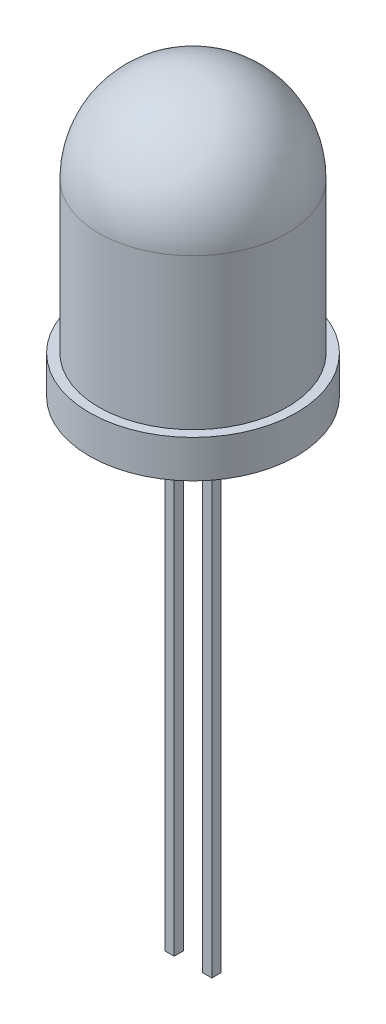
SolidWorks part; units mm, degrees
ref_plane "Front Plane" through (0, 0, 0) normal (0, 0, 1) x (1, 0, 0)
ref_plane "Top Plane" through (0, 0, 0) normal (0, 1, 0) x (1, 0, 0)
ref_plane "Right Plane" through (0, 0, 0) normal (1, 0, 0) x (0, 0, -1)
sketch "Sketch1" plane through (0, 0, 0) normal (0, 1, 0) x (1, 0, 0)
  circle A0 centre (0, 0) radius 5.5
  dimension "D1" = 11
extrude "Boss-Extrude1" add sketch "Sketch1" along normal blind 2
sketch "Sketch2" plane through (0, 2, 0) normal (0, 1, 0) x (1, 0, 0)
  circle A0 centre (0, 0) radius 5
  circle A1 centre (0, 0) radius 5.5 construction
  dimension "D1" = 0.5
extrude "Boss-Extrude2" add sketch "Sketch2" along normal blind 8
sketch "Sketch3" plane through (0, 10, 0) normal (0, 1, 0) x (1, 0, 0)
  line L0 (0, 5) -> (0, -5) construction
  line L1 (0, 5) -> (0, -5)
  circle A0 centre (0, 0) radius 5 construction
  circle A1 centre (0, 0) radius 5 construction
  arc A2 (0, 5) -> (0, -5) centre (0, 0) cw
revolve "Revolve1" add sketch "Sketch3" angle 180 about L1
sketch "Sketch4" plane through (0, 0, 0) normal (0, -1, 0) x (1, 0, 0)
  line L0 (-1, 0) -> (1, 0) construction
  line L2 (-0.75, -0.25) -> (-1.25, -0.25)
  line L3 (-0.75, -0.25) -> (-0.75, 0.25)
  line L4 (-0.75, 0.25) -> (-1.25, 0.25)
  line L5 (-1.25, -0.25) -> (-1.25, 0.25)
  line L6 (-0.75, -0.25) -> (-1.25, 0.25) construction
  line L7 (-0.75, 0.25) -> (-1.25, -0.25) construction
  line L8 (0.75, 0.25) -> (1.25, 0.25)
  line L9 (0.75, 0.25) -> (0.75, -0.25)
  line L10 (0.75, -0.25) -> (1.25, -0.25)
  line L11 (1.25, 0.25) -> (1.25, -0.25)
  line L12 (0.75, 0.25) -> (1.25, -0.25) construction
  line L13 (0.75, -0.25) -> (1.25, 0.25) construction
  point P2 (0, 0)
  dimension "D1" = 2
  dimension "D2" = 0.5
  dimension "D3" = 0.5
  dimension "D4" = 0.5
  dimension "D5" = 0.5
extrude "Boss-Extrude3" add sketch "Sketch4" along normal blind 26
